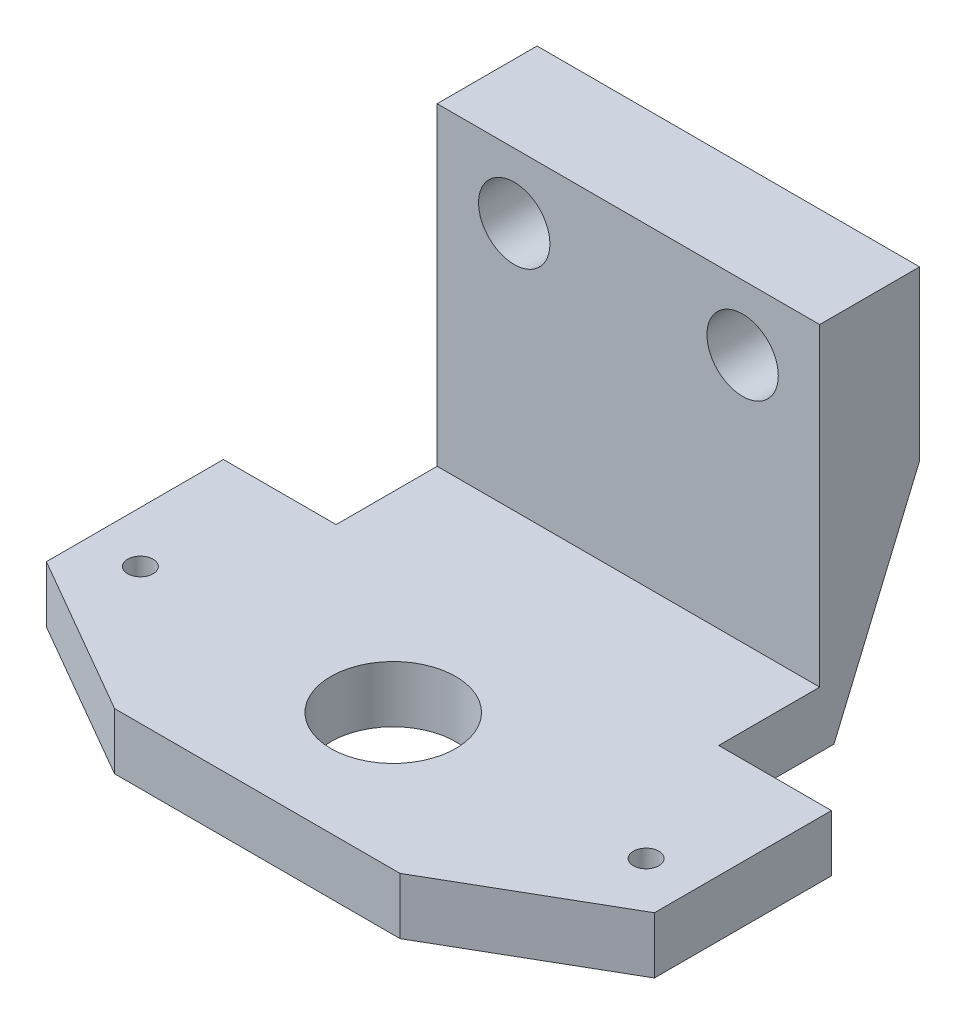
SolidWorks part; units mm, degrees
ref_plane "Front Plane" through (0, 0, 0) normal (0, 0, 1) x (1, 0, 0)
ref_plane "Top Plane" through (0, 0, 0) normal (0, 1, 0) x (1, 0, 0)
ref_plane "Right Plane" through (0, 0, 0) normal (1, 0, 0) x (0, 0, -1)
sketch "Sketch1" plane through (0, 0, 0) normal (0, 1, 0) x (1, 0, 0)
  line L0 (-27.051, 7.874) -> (-17.018, 7.874)
  line L1 (27.051, 7.874) -> (27.051, -7.874)
  line L2 (27.051, -7.874) -> (12.7, -16.1596)
  line L3 (12.7, -16.1596) -> (-12.7, -16.1596)
  line L4 (-12.7, -16.1596) -> (-27.051, -7.874)
  line L5 (-27.051, -7.874) -> (-27.051, 7.874)
  line L6 (-17.018, 7.874) -> (-17.018, 16.8604)
  line L7 (-17.018, 16.8604) -> (17.018, 16.8604)
  line L8 (17.018, 16.8604) -> (17.018, 7.874)
  line L9 (17.018, 7.874) -> (27.051, 7.874)
  line L10 (0, -55) -> (0, 55) construction
  line L11 (-27.051, 0) -> (27.051, 0) construction
  line L14 (-55, 0) -> (55, 0) construction
  point P2 (0, -16.1596)
  point P13 (0, 16.8604)
  point P14 (0, 0)
  dimension "D1" = 25.4
  dimension "D3" = 54.102
  dimension "D4" = 34.036
  dimension "D5" = 33.02
  dimension "D2" = 15.748
  dimension "D6" = 30
extrude "Boss-Extrude1" add sketch "Sketch1" along normal blind 5.0292 contours L0 L6 L7 L8 L9 L1 L2 L3 L4 L5
sketch "Sketch2" plane through (0, 0, 0) normal (0, 1, 0) x (1, 0, 0)
  line L0 (0, -18.1331) -> (0, 18.1331) construction
  line L1 (17.018, 25.7504) -> (-17.018, 25.7504)
  line L2 (17.018, 25.7504) -> (17.018, 16.8604)
  line L3 (17.018, 16.8604) -> (-17.018, 16.8604)
  line L4 (-17.018, 25.7504) -> (-17.018, 16.8604)
  line L5 (17.018, 25.7504) -> (-17.018, 16.8604) construction
  line L6 (17.018, 16.8604) -> (-17.018, 25.7504) construction
  point P0 (0, 21.3054)
  dimension "D1" = 8.89
extrude "Boss-Extrude2" add sketch "Sketch2" along normal blind 32.9692
sketch "Sketch3" plane through (17.018, 0, 0) normal (1, 0, 0) x (0, 0, -1)
  line L0 (25.7504, 32.9692) -> (25.7504, 0) construction
  line L1 (16.8604, 32.9692) -> (25.7504, 32.9692) construction
  line L2 (23.0505, 0) -> (-23.0505, 0) construction
  line L3 (25.7504, 18.034) -> (18.1304, 0)
  point P0 (25.7504, 18.034)
  point P5 (18.1304, 0)
  dimension "D1" = 14.9352
  dimension "D2" = 7.62
extrude "Cut-Extrude1" cut sketch "Sketch3" against normal through all and the other way through all
sketch "Sketch4" plane through (0, 0, -16.8604) normal (0, 0, 1) x (1, 0, 0)
  line L0 (-10.16, 27.178) -> (10.16, 27.178)
  line L1 (0, -18.1331) -> (0, 18.1331) construction
  line L2 (-17.018, 32.9692) -> (17.018, 32.9692) construction
  point P0 (-10.16, 27.178)
  point P1 (10.16, 27.178)
  point P2 (0, 27.178)
  dimension "D1" = 20.32
  dimension "D2" = 5.7912
hole_wizard "1/4 (0.25) Diameter Hole1" positions "Sketch5" profile "Sketch6" hole size "1/4" standard "ANSI Inch" end condition through all
sketch "Sketch5" plane through (0, 0, -16.8604) normal (0, 0, 1) x (1, 0, 0)
  point P0 (-10.16, 27.178)
  point P3 (10.16, 27.178)
sketch "Sketch6" plane through (-10.16, 27.178, -16.8604) normal (1, 0, 0) x (0, -1, 0)
  line L0 (0, 0) -> (0, 8.89)
  line L1 (0, 8.89) -> (3.175, 8.89)
  line L2 (3.175, 8.89) -> (3.175, 0)
  line L5 (3.175, 0) -> (0, 0)
  line L11 (0, -6.35) -> (0, 107.95) construction
  dimension "Thru Hole Dia." = 6.35
  dimension "Thru Hole Depth" = 8.89
sketch "Sketch7" plane through (0, 5.0292, 0) normal (0, 1, 0) x (1, 0, 0)
  line L0 (0, -18.1331) -> (0, 18.1331) construction
  line L1 (-27.051, -7.874) -> (-27.051, 7.874) construction
  circle A0 centre (0, -4.064) radius 5.5562
  point P0 (0, -4.064)
  point P5 (-27.051, -4.064)
  dimension "D1" = 11.1125
  dimension "D2" = 3.81
extrude "Cut-Extrude2" cut sketch "Sketch7" against normal through all contours A0
sketch "Sketch8" plane through (0, 5.0292, 0) normal (0, 1, 0) x (1, 0, 0)
  line L2 (22.5, -4.064) -> (-22.5, -4.064) construction
  line L3 (0, -18.1331) -> (0, 18.1331) construction
  circle A0 centre (0, -4.064) radius 5.5563 construction
  point P0 (0, 0)
  point P1 (0, 0)
  point P6 (0, -4.064)
  point P9 (0, 0)
  dimension "D1" = 3.81
  dimension "D2" = 45
hole_wizard "#4-40 Tapped Hole1" positions "Sketch9" profile "Sketch10" tap size "#4-40" standard "ANSI Inch" end condition through all
sketch "Sketch9" plane through (0, 5.0292, 0) normal (0, 1, 0) x (1, 0, 0)
  point P0 (0, 0)
  point P12 (-22.5, -4.064)
  point P16 (22.5, -4.064)
sketch "Sketch10" plane through (0, 5.0292, 0) normal (1, 0, 0) x (0, 0, 1)
  line L0 (0, 0) -> (0, 5.0292)
  line L1 (0, 5.0292) -> (1.1303, 5.0292)
  line L2 (1.1303, 5.0292) -> (1.1303, 0)
  line L5 (1.1303, 0) -> (0, 0)
  line L11 (0, -6.35) -> (0, 107.95) construction
  dimension "Thru Tap Drill Dia." = 2.2606
  dimension "Thru Tap Drill Depth" = 5.0292
cosmetic thread "Hole Thread1" parameters "D2"=2.8448
cosmetic thread "Hole Thread2" parameters "D2"=2.8448
sketch "Sketch11" [suppressed] plane through (0, 5.0292, 0) normal (0, 1, 0) x (1, 0, 0)
  line L0 (17.018, 16.8604) -> (17.018, 7.874) construction
  line L1 (-27.051, 7.874) -> (-17.018, 7.874)
  line L2 (-27.051, 7.874) -> (-27.051, -16.1596)
  line L3 (-27.051, -16.1596) -> (-17.018, -16.1596)
  line L4 (-17.018, 7.874) -> (-17.018, -16.1596)
  line L5 (27.051, 7.874) -> (17.018, 7.874)
  line L6 (27.051, 7.874) -> (27.051, -16.1596)
  line L7 (27.051, -16.1596) -> (17.018, -16.1596)
  line L8 (17.018, 7.874) -> (17.018, -16.1596)
  line L9 (-17.018, 7.874) -> (-17.018, 16.8604) construction
  line L10 (12.7, -16.1596) -> (-12.7, -16.1596) construction
extrude "Cut-Extrude3" [suppressed] cut sketch "Sketch11" against normal through all
equation "\"angle\"= 30"
equation "\"D6@Sketch1\"=\"angle\""
equation "\"chamfer offset\"= 0.3in"
equation "\"D2@Sketch3\"=\"chamfer offset\""
equation "\"hole height\"= 0.228in"
equation "\"D2@Sketch4\"=\"hole height\""
equation "\"Large hole offset\"= 0.15in"
equation "\"D2@Sketch7\"=\"Large hole offset\""
